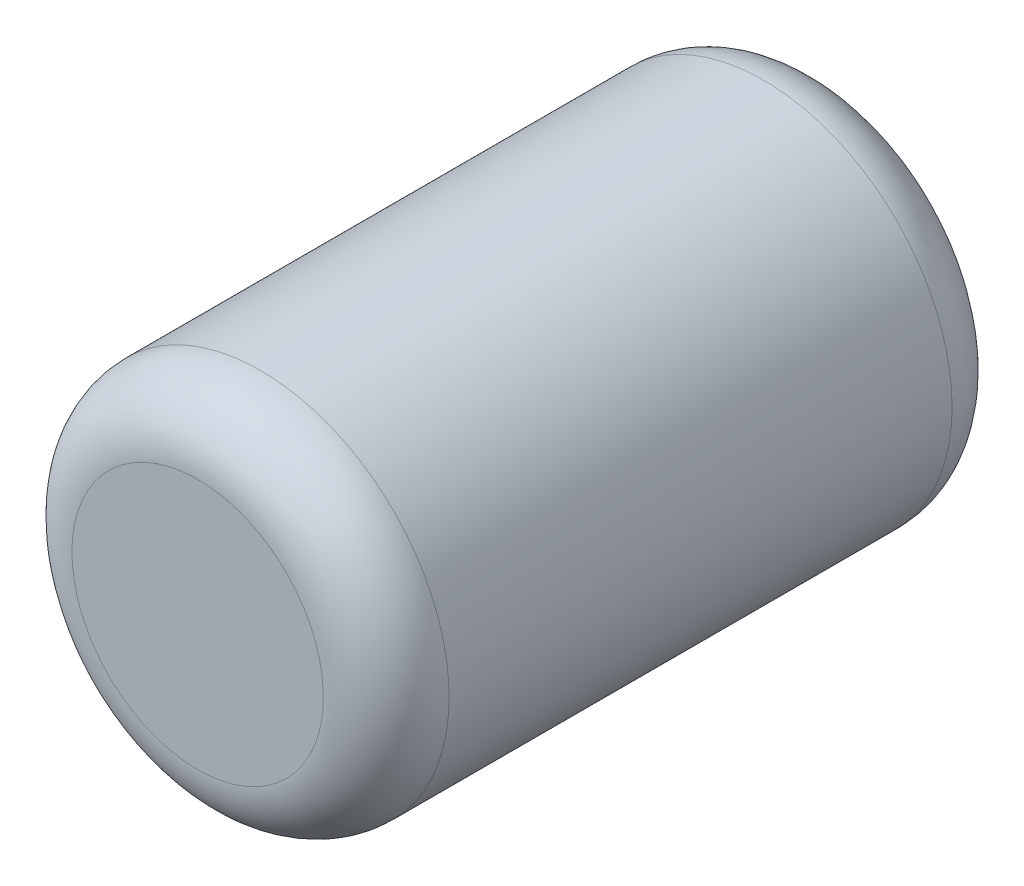
SolidWorks part; units mm, degrees
material "Простая углеродистая сталь"
ref_plane "Front" through (0, 0, 0) normal (0, 0, 1) x (1, 0, 0)
ref_plane "Top" through (0, 0, 0) normal (0, 1, 0) x (1, 0, 0)
ref_plane "Right" through (0, 0, 0) normal (1, 0, 0) x (0, 0, -1)
sketch "Эскиз2" plane through (0, 0, 0) normal (1, 0, 0) x (0, 0, -1)
  line L0 (0, 0) -> (-9.8044, 0) construction
  line L1 (0, 0) -> (-5, 0)
  line L2 (0, 0) -> (0, -1)
  line L3 (-0.5, -1.5) -> (-4.5, -1.5)
  line L4 (-5, -1) -> (-5, 0)
  arc A0 (0, -1) -> (-0.5, -1.5) centre (-0.5, -1) cw
  arc A1 (-4.5, -1.5) -> (-5, -1) centre (-4.5, -1) cw
  dimension "D1" = 3
  dimension "D3" = 0.5
  dimension "D2" = 5
revolve "Повернуть1" add sketch "Эскиз2" angle 360 about L0
